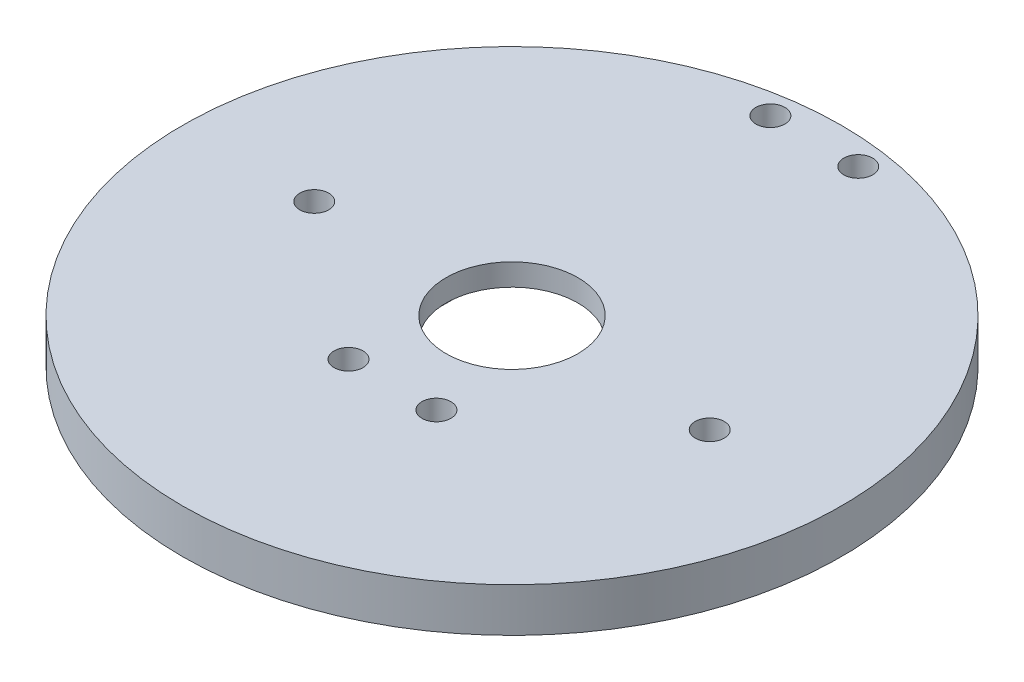
SolidWorks part; units mm, degrees
material "Alliage 1060"
ref_plane "Plan de face" through (0, 0, 0) normal (0, 0, 1) x (1, 0, 0)
ref_plane "Plan de dessus" through (0, 0, 0) normal (0, 1, 0) x (1, 0, 0)
ref_plane "Plan de droite" through (0, 0, 0) normal (1, 0, 0) x (0, 0, -1)
sketch "Esquisse1" plane through (0, 0, 0) normal (0, 1, 0) x (1, 0, 0)
  circle A0 centre (0, 0) radius 37.5
  dimension "D1" = 75
extrude "Extrusion1" add sketch "Esquisse1" against normal blind 5
sketch "Esquisse6" plane through (0, -5, 0) normal (0, -1, 0) x (1, 0, 0)
  line L1 (-9.95, 1) -> (-9.95, -21.8)
  line L2 (-0.95, 10) -> (0.95, 10)
  line L3 (9.95, 1) -> (9.95, -21.8)
  line L4 (-0.95, -30.8) -> (0.95, -30.8)
  line L8 (9.95, 8) -> (9.95, -28.8) construction
  line L9 (-7.95, 10) -> (7.95, 10) construction
  line L10 (-9.95, -28.8) -> (-9.95, 8) construction
  line L11 (7.95, -30.8) -> (-7.95, -30.8) construction
  arc A0 (0.95, -30.8) -> (9.95, -21.8) centre (0.95, -21.8) ccw
  arc A1 (9.95, 1) -> (0.95, 10) centre (0.95, 1) ccw
  arc A2 (-0.95, 10) -> (-9.95, 1) centre (-0.95, 1) ccw
  arc A3 (-9.95, -21.8) -> (-0.95, -30.8) centre (-0.95, -21.8) ccw
  dimension "D1" = 9
extrude "Enlèv. mat.-Extru.2" cut sketch "Esquisse6" against normal blind 2.5
sketch "Esquisse7" plane through (0, -2.5, 0) normal (0, -1, 0) x (1, 0, 0)
  circle A0 centre (0, 0) radius 7.5
  circle A1 centre (0, 0) radius 2.9 construction
  dimension "D1" = 15
extrude "Enlèv. mat.-Extru.3" cut sketch "Esquisse7" against normal through all
hole_wizard "Trou taraudé M4x0.71" positions "Esquisse9" profile "Esquisse8" tap size "M4x0.7" standard "Ansi Métrique" end condition through all
sketch "Esquisse9" plane through (0, -5, 0) normal (0, -1, 0) x (1, 0, 0)
  line L0 (-22.5, 0) -> (22.5, 0) construction
  arc A0 (-6.5068, 14.9151) -> (-3.4932, 14.9151) centre (-5, 13.6) ccw construction
  arc A1 (3.4932, 14.9151) -> (6.5068, 14.9151) centre (5, 13.6) ccw construction
  arc A2 (-3.4932, -35.7151) -> (-6.5068, -35.7151) centre (-5, -34.4) ccw construction
  arc A3 (6.5068, -35.7151) -> (3.4932, -35.7151) centre (5, -34.4) ccw construction
  point P0 (-5, -34.4)
  point P1 (5, -34.4)
  point P3 (-5, 13.6)
  point P5 (5, 13.6)
  point P22 (22.5, 0)
  point P24 (-22.5, 0)
  dimension "D1" = 45
sketch "Esquisse8" plane through (-5, -5, -34.4) normal (1, 0, 0) x (0, 0, -1)
  line L0 (0, 0) -> (0, 5)
  line L1 (0, 5) -> (1.65, 5)
  line L2 (1.65, 5) -> (1.65, 0)
  line L5 (1.65, 0) -> (0, 0)
  line L11 (0, -6.35) -> (0, 107.95) construction
  dimension "Diamètre du trou pour taraudage jusqu'au prochain" = 3.3
  dimension "Profondeur du trou pour taraudage jusqu'au prochain" = 5
cosmetic thread "Filetage de perçage1" parameters "D2"=4
cosmetic thread "Filetage de perçage2" parameters "D2"=4
cosmetic thread "Filetage de perçage3" parameters "D2"=4
cosmetic thread "Filetage de perçage4" parameters "D2"=4
cosmetic thread "Filetage de perçage5" parameters "D2"=4
cosmetic thread "Filetage de perçage6" parameters "D2"=4
